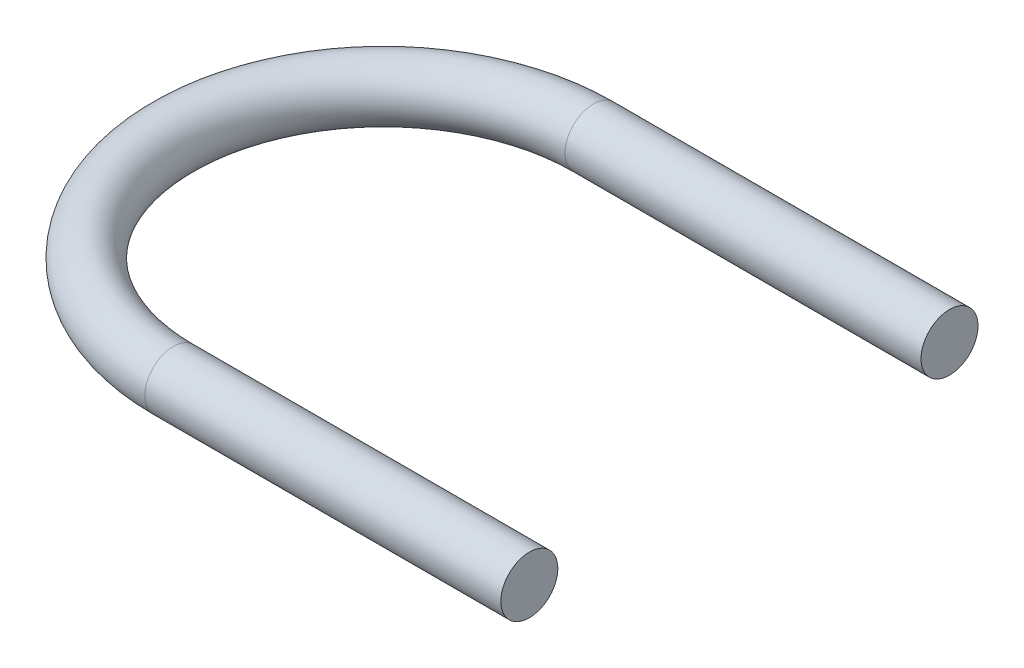
SolidWorks part; units mm, degrees
ref_plane "Front" through (0, 0, 0) normal (0, 0, 1) x (1, 0, 0)
ref_plane "Top" through (0, 0, 0) normal (0, 1, 0) x (1, 0, 0)
ref_plane "Right" through (0, 0, 0) normal (1, 0, 0) x (0, 0, -1)
sketch "Sketch2" plane through (0, 0, 0) normal (0, 1, 0) x (1, 0, 0)
  line L0 (0, 29.5) -> (50, 29.5)
  line L1 (0, -29.5) -> (50, -29.5)
  arc A0 (0, 29.5) -> (0, -29.5) centre (0, 0) ccw
  dimension "D1" = 50
  dimension "D3" = 29.5
  dimension "D2" = 50
ref_plane "Plane1" through (50, 0, 0) normal (1, 0, 0) x (0, 0, -1)
sweep "Sweep2" add path "Sketch2" circular profile diameter 8 parameters "D3"=8
